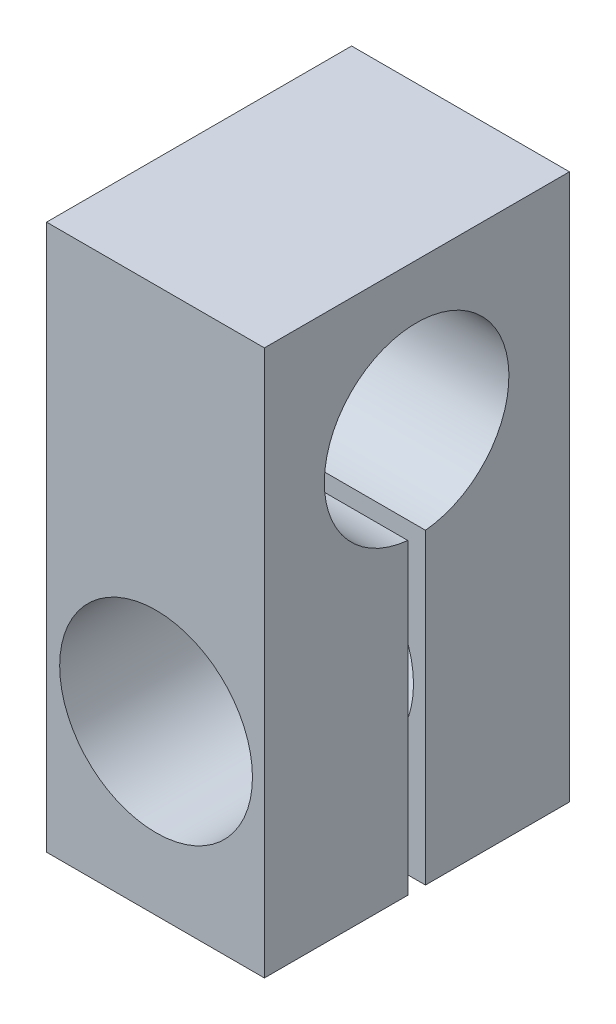
SolidWorks part; units mm, degrees
ref_plane "Front Plane" through (0, 0, 0) normal (0, 0, 1) x (1, 0, 0)
ref_plane "Top Plane" through (0, 0, 0) normal (0, 1, 0) x (1, 0, 0)
ref_plane "Right Plane" through (0, 0, 0) normal (1, 0, 0) x (0, 0, -1)
sketch "Sketch1" plane through (0, 0, 0) normal (1, 0, 0) x (0, 0, -1)
  line L0 (1.5561, -9.9154) -> (3.9177, -9.9163)
  line L1 (1.5561, -0.9285) -> (1.5561, -9.9154)
  line L2 (6.5797, -9.9174) -> (6.5797, -0.9285)
  line L3 (4.2083, -9.9164) -> (6.5797, -9.9174)
  line L8 (1.5561, -0.9285) -> (6.5797, -0.9285)
  line L9 (3.9177, -4.8555) -> (3.9177, -9.9163)
  line L11 (4.2083, -4.8555) -> (4.2083, -9.9164)
  arc A0 (4.2083, -4.8555) -> (3.9177, -4.8555) centre (4.0628, -3.3424) ccw
extrude "Boss-Extrude1" add sketch "Sketch1" along normal blind 3.5875
sketch "Sketch2" plane through (0, 0, -1.5561) normal (0, 0, 1) x (1, 0, 0)
  circle A0 centre (1.8033, -7.1493) radius 1.5875
  point P2 (1.8056, -6.7387)
  point P3 (1.8033, -7.1493)
extrude "Cut-Extrude1" cut sketch "Sketch2" against normal blind 5.5875
